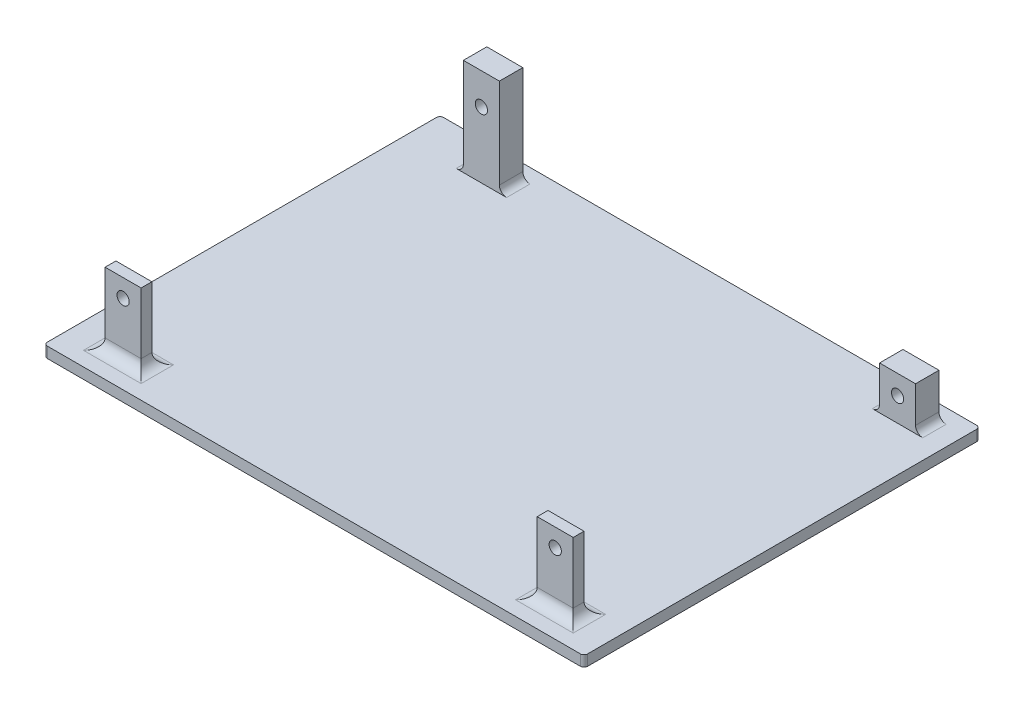
SolidWorks part; units mm, degrees
ref_plane "Front Plane" through (0, 0, 0) normal (0, 0, 1) x (1, 0, 0)
ref_plane "Top Plane" through (0, 0, 0) normal (0, 1, 0) x (1, 0, 0)
ref_plane "Right Plane" through (0, 0, 0) normal (1, 0, 0) x (0, 0, -1)
sketch "Sketch1" plane through (0, 0, 0) normal (0, 1, 0) x (1, 0, 0)
  line L1 (75, 55) -> (-75, 55)
  line L2 (75, 55) -> (75, -55)
  line L3 (75, -55) -> (-75, -55)
  line L4 (-75, 55) -> (-75, -55)
  line L5 (75, 55) -> (-75, -55) construction
  line L6 (75, -55) -> (-75, 55) construction
  point P0 (0, 0)
  dimension "D1" = 110
  dimension "D2" = 150
extrude "Boss-Extrude1" add sketch "Sketch1" along normal mid plane 3
sketch "Sketch2" plane through (0, 1.5, 0) normal (0, 1, 0) x (1, 0, 0)
  line L0 (75, 55) -> (-75, 55) construction
  line L1 (57.57, 51) -> (67.57, 51)
  line L2 (57.57, 51) -> (57.57, 44.5)
  line L3 (57.57, 44.5) -> (67.57, 44.5)
  line L4 (67.57, 51) -> (67.57, 44.5)
  line L5 (57.57, 51) -> (67.57, 44.5) construction
  line L6 (57.57, 44.5) -> (67.57, 51) construction
  line L7 (75, -55) -> (75, 55) construction
  line L9 (-58, 51) -> (-48, 51)
  line L10 (-58, 51) -> (-58, 44.5)
  line L11 (-58, 44.5) -> (-48, 44.5)
  line L12 (-48, 51) -> (-48, 44.5)
  line L13 (-58, 51) -> (-48, 44.5) construction
  line L14 (-58, 44.5) -> (-48, 51) construction
  line L15 (-75, 55) -> (-75, -55) construction
  point P0 (62.57, 47.75)
  point P9 (-53, 47.75)
  dimension "D1" = 4
  dimension "D2" = 10
  dimension "D3" = 6.5
  dimension "D4" = 12.43
  dimension "D5" = 6.5
  dimension "D6" = 10
  dimension "D7" = 22
extrude "Boss-Extrude2" add sketch "Sketch2" along normal blind 12
sketch "Sketch3" plane through (0, 13.5, 0) normal (0, 1, 0) x (1, 0, 0)
  line L1 (-58, 44.5) -> (-48, 44.5)
  line L2 (-58, 44.5) -> (-58, 51)
  line L3 (-58, 51) -> (-48, 51)
  line L4 (-48, 44.5) -> (-48, 51)
extrude "Boss-Extrude3" add sketch "Sketch3" along normal blind 15 contours L2 L1 L4 L3
hole_wizard "M3 Clearance Hole1" positions "Sketch4" profile "Sketch5" hole size "M3" standard "ISO" end condition through all
sketch "Sketch4" plane through (0, 0, -44.5) normal (0, 0, 1) x (1, 0, 0)
  line L0 (-53, 28.5) -> (-53, 26.0125) construction
  line L1 (-58, 28.5) -> (-48, 28.5) construction
  line L3 (-75, 1.5) -> (75, 1.5) construction
  point P0 (-53, 19.77)
  dimension "D1" = 18.27
sketch "Sketch5" plane through (-53, 19.77, -44.5) normal (1, 0, 0) x (0, -1, 0)
  line L0 (0, 0) -> (0, 10.5)
  line L1 (0, 10.5) -> (1.7, 10.5)
  line L2 (1.7, 10.5) -> (1.7, 0)
  line L5 (1.7, 0) -> (0, 0)
  line L11 (0, -6.35) -> (0, 107.95) construction
  dimension "Thru Hole Dia." = 3.4
  dimension "Thru Hole Depth" = 10.5
fillet "Fillet1" radius 2 4 edges at (67.57, 1.5, -47.75) (57.57, 1.5, -47.75) (-58, 1.5, -47.75) (-48, 1.5, -47.75)
hole_wizard "M3 Clearance Hole2" positions "Sketch6" profile "Sketch7" hole size "M3" standard "ISO" end condition through all
sketch "Sketch6" plane through (0, 0, -44.5) normal (0, 0, 1) x (1, 0, 0)
  line L0 (55.57, 1.5) -> (69.57, 1.5) construction
  line L1 (62.57, 13.5) -> (62.57, 10.699) construction
  line L2 (57.57, 13.5) -> (67.57, 13.5) construction
  point P0 (62.57, 8.09)
  dimension "D1" = 6.59
sketch "Sketch7" plane through (62.57, 8.09, -44.5) normal (1, 0, 0) x (0, -1, 0)
  line L0 (0, 0) -> (0, 10.5)
  line L1 (0, 10.5) -> (1.7, 10.5)
  line L2 (1.7, 10.5) -> (1.7, 0)
  line L5 (1.7, 0) -> (0, 0)
  line L11 (0, -6.35) -> (0, 107.95) construction
  dimension "Thru Hole Dia." = 3.4
  dimension "Thru Hole Depth" = 10.5
sketch "Sketch8" plane through (0, 1.5, 0) normal (0, 1, 0) x (1, 0, 0)
  line L0 (-75, -55) -> (75, -55) construction
  line L1 (-65, -45) -> (-55, -45)
  line L2 (-65, -45) -> (-65, -48)
  line L3 (-65, -48) -> (-55, -48)
  line L4 (-55, -45) -> (-55, -48)
  line L5 (-65, -45) -> (-55, -48) construction
  line L6 (-65, -48) -> (-55, -45) construction
  line L10 (-75, 55) -> (-75, -55) construction
  point P0 (-60, -46.5)
  dimension "D1" = 7
  dimension "D2" = 10
  dimension "D3" = 3
  dimension "D4" = 15
extrude "Boss-Extrude4" add sketch "Sketch8" along normal blind 20
fillet "Fillet2" radius 3 4 edges at (-65, 1.5, 46.5) (-55, 1.5, 46.5) (-60, 1.5, 48) (-60, 1.5, 45)
hole_wizard "M3 Clearance Hole3" positions "Sketch9" profile "Sketch10" hole size "M3" standard "ISO" end condition up to next
sketch "Sketch9" plane through (0, 0, 48) normal (0, 0, 1) x (1, 0, 0)
  line L0 (-60, 21.5) -> (-60, 19.8135) construction
  line L1 (-65, 21.5) -> (-55, 21.5) construction
  line L3 (-68, 1.5) -> (-52, 1.5) construction
  point P0 (-60, 16.5)
  dimension "D1" = 15
sketch "Sketch10" plane through (-60, 16.5, 48) normal (1, 0, 0) x (0, -1, 0)
  line L0 (0, 0) -> (0, 3)
  line L1 (0, 3) -> (1.7, 3)
  line L2 (1.7, 3) -> (1.7, 0)
  line L5 (1.7, 0) -> (0, 0)
  line L11 (0, -6.35) -> (0, 107.95) construction
  dimension "Thru Hole Dia." = 3.4
  dimension "Thru Hole Depth" = 3
mirror "Mirror1" about plane through (0, 0, 0) normal (1, 0, 0) of "Boss-Extrude4", "Fillet2", "M3 Clearance Hole3"
fillet "Fillet3" radius 1 4 edges at (-75, 0, -55) (-75, 0, 55) (75, 0, 55) (75, 0, -55)
